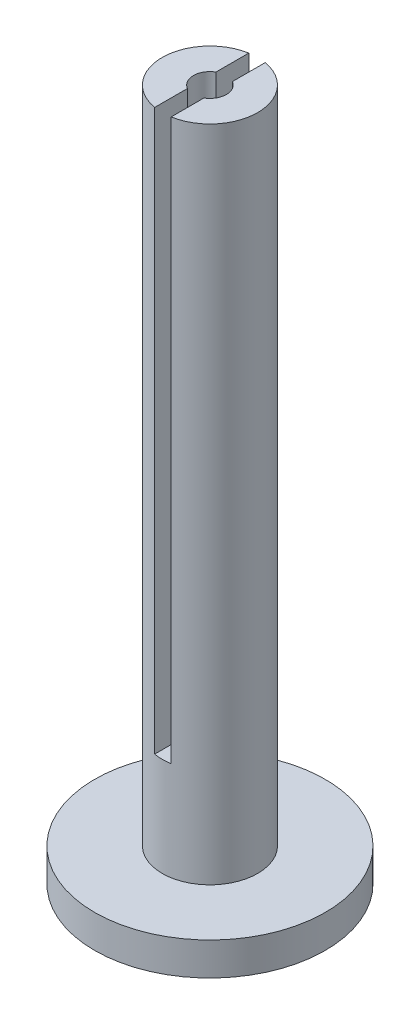
SolidWorks part; units mm, degrees
ref_plane "Vorne" through (0, 0, 0) normal (0, 0, 1) x (1, 0, 0)
ref_plane "Oben" through (0, 0, 0) normal (0, 1, 0) x (1, 0, 0)
ref_plane "Rechts" through (0, 0, 0) normal (1, 0, 0) x (0, 0, -1)
sketch "Skizze1" plane through (0, 0, 0) normal (0, 1, 0) x (1, 0, 0)
  circle A0 centre (0, 0) radius 3.5
  dimension "D1" = 7
extrude "Aufsatz-Linear austragen1" add sketch "Skizze1" along normal blind 1
sketch "Skizze2" plane through (0, 1, 0) normal (0, 1, 0) x (1, 0, 0)
  circle A0 centre (0, 0) radius 1.45
  dimension "D1" = 2.9
extrude "Aufsatz-Linear austragen2" add sketch "Skizze2" along normal blind 20
sketch "Skizze3" plane through (0, 21, 0) normal (0, 1, 0) x (1, 0, 0)
  line L1 (0.25, 1.5) -> (-0.25, 1.5)
  line L2 (0.25, 1.5) -> (0.25, -1.5)
  line L3 (0.25, -1.5) -> (-0.25, -1.5)
  line L4 (-0.25, 1.5) -> (-0.25, -1.5)
  line L5 (0.25, 1.5) -> (-0.25, -1.5) construction
  line L6 (0.25, -1.5) -> (-0.25, 1.5) construction
  point P0 (0, 0)
  dimension "D1" = 0.5
  dimension "D2" = 3
extrude "Schnitt-Linear austragen1" cut sketch "Skizze3" against normal blind 17
sketch "Skizze4" plane through (0, 21, 0) normal (0, 1, 0) x (1, 0, 0)
  circle A0 centre (0, 0) radius 0.5
  dimension "D1" = 1
extrude "Schnitt-Linear austragen2" cut sketch "Skizze4" against normal blind 17
